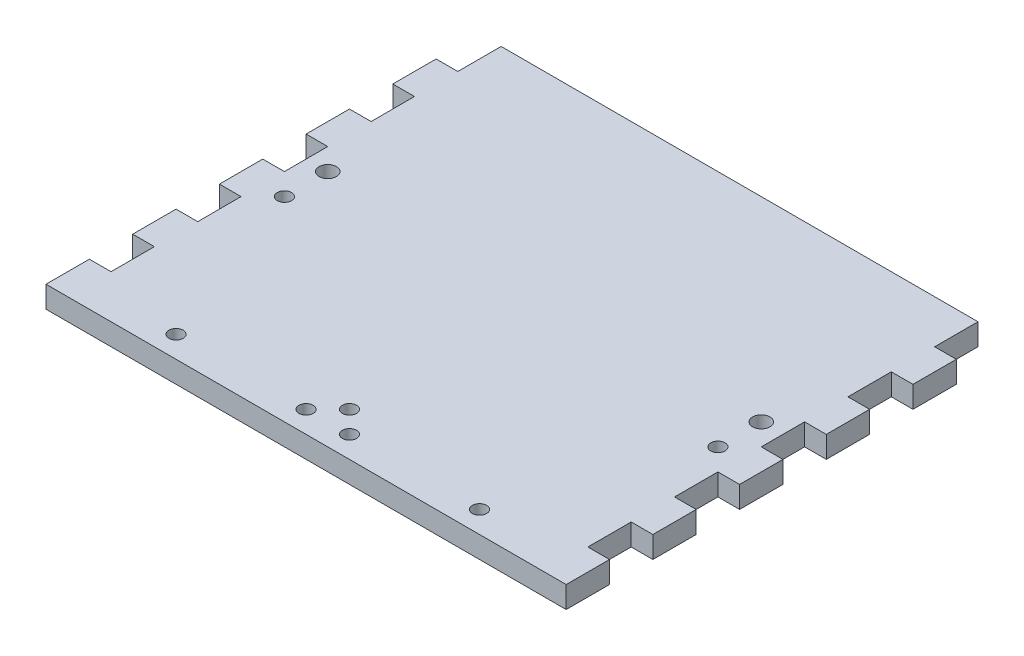
SolidWorks part; units mm, degrees
ref_plane "Front Plane" through (0, 0, 0) normal (0, 0, 1) x (1, 0, 0)
ref_plane "Top Plane" through (0, 0, 0) normal (0, 1, 0) x (1, 0, 0)
ref_plane "Right Plane" through (0, 0, 0) normal (1, 0, 0) x (0, 0, -1)
sketch "Sketch2" plane through (0, 0, 0) normal (0, 1, 0) x (1, 0, 0)
  line L0 (3.175, 13.2292) -> (3.175, 25.9292)
  line L1 (3.175, 13.2292) -> (-3.175, 13.2292)
  line L2 (-3.175, 13.2292) -> (-3.175, 0.5292)
  line L3 (3.175, 25.9292) -> (-3.175, 25.9292)
  line L4 (-3.175, 25.9292) -> (-3.175, 38.6292)
  line L5 (-3.175, 38.6292) -> (3.175, 38.6292)
  line L6 (3.175, 51.3292) -> (-3.175, 51.3292)
  line L7 (-3.175, 51.3292) -> (-3.175, 64.0292)
  line L8 (-3.175, 64.0292) -> (3.175, 64.0292)
  line L9 (3.175, 76.7292) -> (-3.175, 76.7292)
  line L10 (3.175, 38.6292) -> (3.175, 51.3292)
  line L11 (-3.175, 76.7292) -> (-3.175, 89.4292)
  line L12 (-3.175, 89.4292) -> (3.175, 89.4292)
  line L13 (3.175, 102.1292) -> (-3.175, 102.1292)
  line L14 (3.175, 64.0292) -> (3.175, 76.7292)
  line L15 (-3.175, 102.1292) -> (-3.175, 114.8292)
  line L16 (-3.175, 114.8292) -> (3.175, 114.8292)
  line L17 (73.025, 0.5292) -> (73.025, 13.2292) construction
  line L18 (3.175, 89.4292) -> (3.175, 102.1292)
  line L19 (73.025, 6.8792) -> (79.375, 6.8792) construction
  line L20 (73.025, 6.8792) -> (66.675, 6.8792) construction
  line L21 (-3.175, 0.5292) -> (149.225, 0.5292)
  line L22 (3.175, 114.8292) -> (3.175, 127.5292)
  line L23 (73.025, 0.5292) -> (73.025, 127.5292) construction
  line L24 (117.475, 13.2292) -> (117.475, 6.8792) construction
  line L25 (142.875, 13.2292) -> (117.475, 13.2292) construction
  line L26 (3.175, 70.3792) -> (9.525, 70.3792) construction
  line L27 (142.875, 70.3792) -> (136.525, 70.3792) construction
  line L28 (142.875, 114.8292) -> (142.875, 127.5292)
  line L31 (142.875, 89.4292) -> (142.875, 102.1292)
  line L33 (149.225, 114.8292) -> (142.875, 114.8292)
  line L34 (149.225, 102.1292) -> (149.225, 114.8292)
  line L35 (142.875, 64.0292) -> (142.875, 76.7292)
  line L36 (142.875, 102.1292) -> (149.225, 102.1292)
  line L37 (149.225, 89.4292) -> (142.875, 89.4292)
  line L38 (149.225, 76.7292) -> (149.225, 89.4292)
  line L39 (142.875, 38.6292) -> (142.875, 51.3292)
  line L40 (142.875, 76.7292) -> (149.225, 76.7292)
  line L41 (149.225, 64.0292) -> (142.875, 64.0292)
  line L42 (149.225, 51.3292) -> (149.225, 64.0292)
  line L43 (142.875, 51.3292) -> (149.225, 51.3292)
  line L44 (149.225, 38.6292) -> (142.875, 38.6292)
  line L45 (149.225, 25.9292) -> (149.225, 38.6292)
  line L46 (142.875, 25.9292) -> (149.225, 25.9292)
  line L47 (149.225, 13.2292) -> (149.225, 0.5292)
  line L48 (142.875, 13.2292) -> (149.225, 13.2292)
  line L49 (3.175, 13.2292) -> (28.575, 13.2292) construction
  line L50 (28.575, 13.2292) -> (28.575, 6.8792) construction
  line L51 (142.875, 13.2292) -> (142.875, 25.9292)
  line L53 (3.175, 127.5292) -> (142.875, 127.5292)
  circle A0 centre (136.525, 57.6792) radius 2.0828
  circle A1 centre (28.575, 6.8792) radius 2.0828
  circle A2 centre (9.525, 57.6792) radius 2.0828
  circle A3 centre (117.475, 6.8792) radius 2.0828
  circle A4 centre (79.375, 6.8792) radius 2.0828
  circle A5 centre (73.025, 13.2292) radius 2.0828
  circle A6 centre (66.675, 6.8792) radius 2.0828
  circle A7 centre (9.525, 70.3792) radius 2.54
  circle A8 centre (136.525, 70.3792) radius 2.54
extrude "Boss-Extrude1" add sketch "Sketch2" along normal blind 6.35
